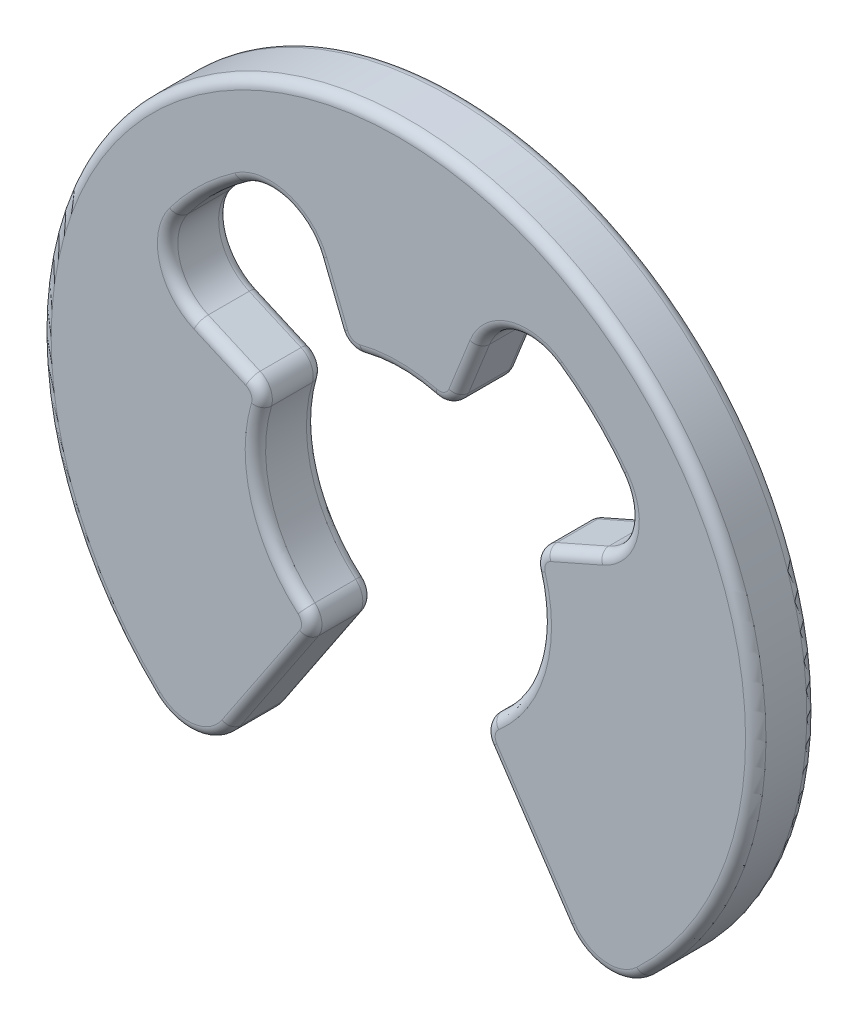
SolidWorks part; units mm, degrees
ref_plane "前视基准面" through (0, 0, 0) normal (0, 0, 1) x (1, 0, 0)
ref_plane "上视基准面" through (0, 0, 0) normal (0, 1, 0) x (1, 0, 0)
ref_plane "右视基准面" through (0, 0, 0) normal (1, 0, 0) x (0, 0, -1)
sketch "草图1" plane through (0, 0, 0) normal (0, 0, 1) x (1, 0, 0)
  line L0 (-0.5185, 1.3004) -> (-1, 2.508)
  line L1 (0.5185, 1.3004) -> (1, 2.508)
  line L2 (-0.7778, -1.1641) -> (-1.9444, -2.9102)
  line L3 (0.7778, -1.1641) -> (1.9444, -2.9102)
  line L4 (-1.2814, 0.5638) -> (-2.4714, 1.0874)
  line L5 (1.2814, 0.5638) -> (2.4714, 1.0874)
  arc A0 (1.9444, -2.9102) -> (-1.9444, -2.9102) centre (0, 0) ccw
  arc A1 (0.7778, -1.1641) -> (1.2814, 0.5638) centre (0, 0) ccw
  circle A2 centre (0, 0) radius 2.7 construction
  arc A3 (-2.4714, 1.0874) -> (-1, 2.508) centre (0, 0) cw
  arc A4 (1, 2.508) -> (2.4714, 1.0874) centre (0, 0) cw
  arc A5 (-1.2814, 0.5638) -> (-0.7778, -1.1641) centre (0, 0) ccw
  arc A6 (0.5185, 1.3004) -> (-0.5185, 1.3004) centre (0, 0) ccw
  point P3 (1.5, -2.245)
  point P9 (-1.5, -2.245)
  dimension "D1" = 7
  dimension "D2" = 2.8
  dimension "D4" = 0.8
  dimension "D3" = 2
  dimension "D5" = 3
  dimension "D6" = 80
extrude "凸台-拉伸1" add sketch "草图1" along normal blind 0.6
fillet "圆角1" radius 0.2 6 edges at (0.7778, -1.1641, 0.3) (1.2814, 0.5638, 0.3) (0.5185, 1.3004, 0.3) (-0.5185, 1.3004, 0.3) (-1.2814, 0.5638, 0.3) (-0.7778, -1.1641, 0.3)
fillet "圆角2" radius 0.5 6 edges at (1.9444, -2.9102, 0.3) (-1.9444, -2.9102, 0.3) (2.4714, 1.0874, 0.3) (1, 2.508, 0.3) (-2.4714, 1.0874, 0.3) (-1, 2.508, 0.3)
fillet "圆角3" radius 0.1 48 edges at (-0.85, -1.1822, 0) (-1.2626, -1.8897, 0) (-2.0029, -2.6786, 0) (0, 3.5, 0) (2.0029, -2.6786, 0) (1.2626, -1.8897, 0) (0.85, -1.1822, 0) (1.3441, -0.3918, 0) (1.3521, 0.5403, 0) (1.707, 0.7511, 0) (2.2433, 1.1937, 0) (1.8754, 1.9424, 0) (1.1143, 2.2838, 0) (0.6907, 1.7323, 0) (0.4925, 1.3702, 0) (0, 1.4, 0) (-0.4925, 1.3702, 0) (-0.6907, 1.7323, 0) (-1.1143, 2.2838, 0) (-1.8754, 1.9424, 0) (-2.2433, 1.1937, 0) (-1.707, 0.7511, 0) (-1.3521, 0.5403, 0) (-0.85, -1.1822, 0.6) (-1.2626, -1.8897, 0.6) (-2.0029, -2.6786, 0.6) (0, 3.5, 0.6) (2.0029, -2.6786, 0.6) (1.2626, -1.8897, 0.6) (0.85, -1.1822, 0.6) (1.3441, -0.3918, 0.6) (1.3521, 0.5403, 0.6) (1.707, 0.7511, 0.6) (2.2433, 1.1937, 0.6) (1.8754, 1.9424, 0.6) (1.1143, 2.2838, 0.6) (0.6907, 1.7323, 0.6) (0.4925, 1.3702, 0.6) (0, 1.4, 0.6) (-0.4925, 1.3702, 0.6) (-0.6907, 1.7323, 0.6) (-1.1143, 2.2838, 0.6) (-1.8754, 1.9424, 0.6) (-2.2433, 1.1937, 0.6) (-1.707, 0.7511, 0.6) (-1.3521, 0.5403, 0.6) (-1.3441, -0.3918, 0) (-1.3441, -0.3918, 0.6)
